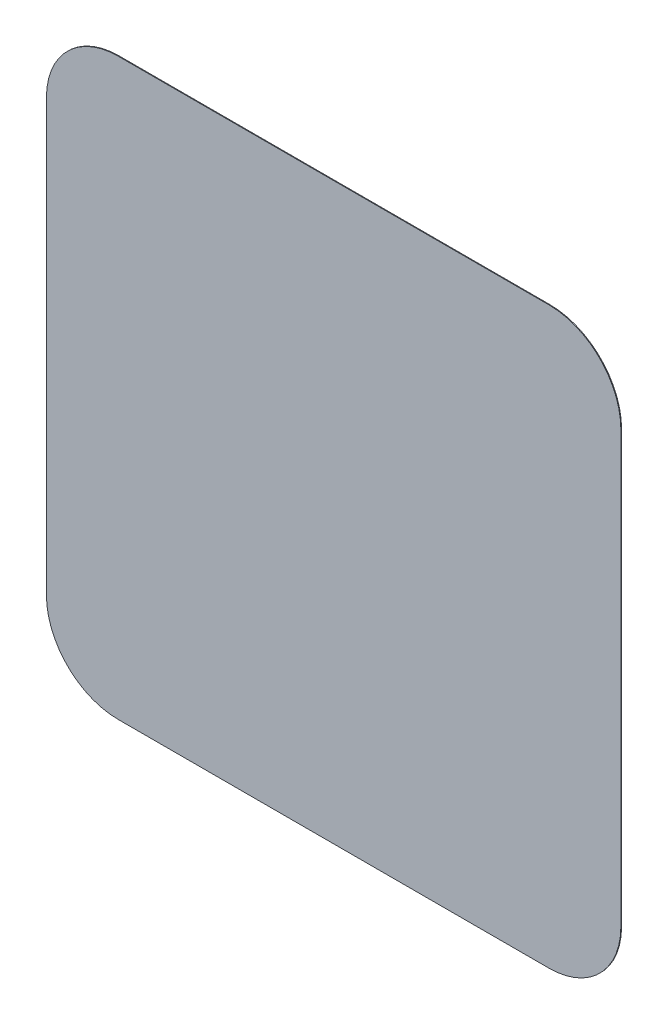
SolidWorks part; units mm, degrees
ref_plane "Front" through (0, 0, 0) normal (0, 0, 1) x (1, 0, 0)
ref_plane "Top" through (0, 0, 0) normal (0, 1, 0) x (1, 0, 0)
ref_plane "Right" through (0, 0, 0) normal (1, 0, 0) x (0, 0, -1)
sketch "Sketch2" plane through (0, 0, 0) normal (0, 0, 1) x (1, 0, 0)
  line L0 (0, -24.4203) -> (0, 35.0295) construction
  line L1 (-4, -4) -> (4, -4)
  line L2 (-4, -4) -> (-4, 4)
  line L3 (-4, 4) -> (4, 4)
  line L4 (4, -4) -> (4, 4)
  line L5 (54.0167, 0) -> (-48.115, 0) construction
  dimension "D1" = 8
  dimension "D2" = 8
extrude "Base-Extrude" add sketch "Sketch2" along normal blind 0.01
fillet "Fillet1" radius 1
